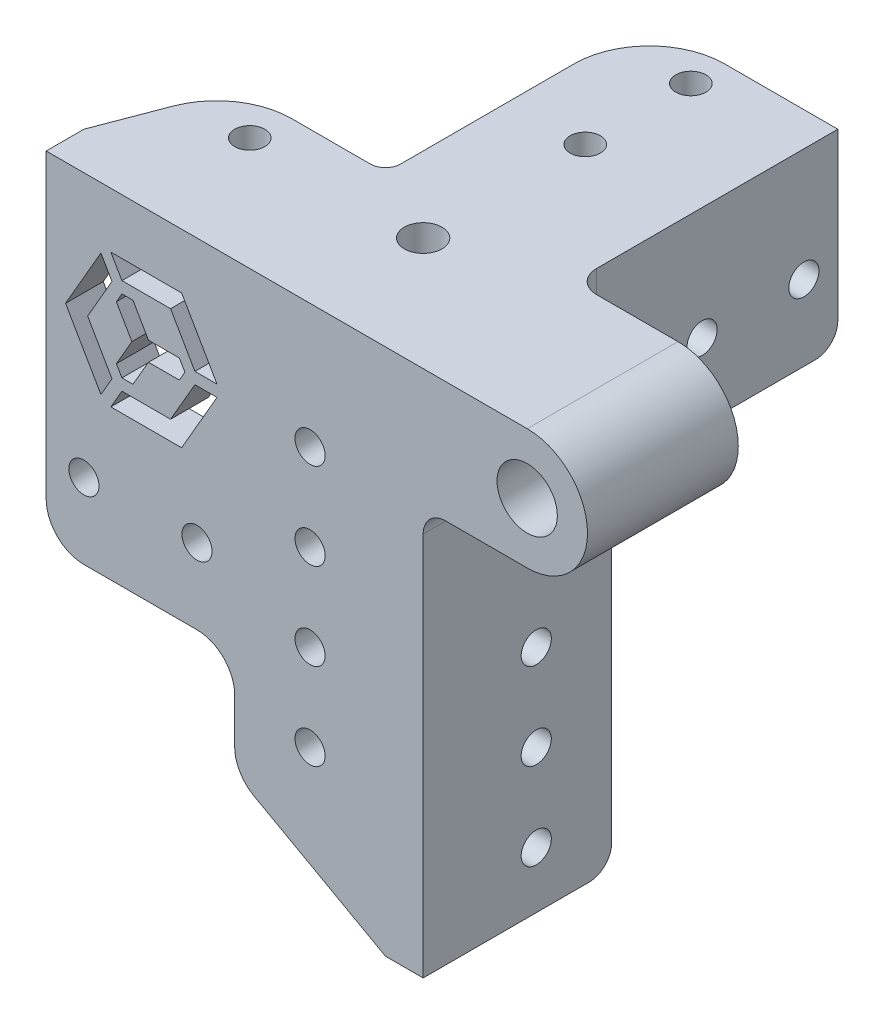
SolidWorks part; units mm, degrees
ref_plane "Front Plane" through (0, 0, 0) normal (0, 0, 1) x (1, 0, 0)
ref_plane "Top Plane" through (0, 0, 0) normal (0, 1, 0) x (1, 0, 0)
ref_plane "Right Plane" through (0, 0, 0) normal (1, 0, 0) x (0, 0, -1)
sketch "Sketch1" plane through (0, 0, 0) normal (0, 0, 1) x (1, 0, 0)
  line L0 (0, 20) -> (-25, 20)
  line L1 (0, 0) -> (-25, 0)
  line L2 (0, 0) -> (0, -20)
  line L3 (0, -20) -> (-25, -20)
  line L4 (-25, 0) -> (-25, -20)
  line L5 (0, 20) -> (20, 20)
  line L6 (0, 20) -> (0, -33.8889)
  line L8 (20, 20) -> (20, -45)
  line L9 (-25, 20) -> (-25, 0)
  line L11 (20, 20) -> (25, 20)
  line L12 (25, 20) -> (25, -45)
  line L13 (25, -45) -> (20, -45)
  line L14 (38.8, 25) -> (25, 25)
  line L15 (-25, 20) -> (25, 20)
  line L16 (-25, 20) -> (-25, 25)
  line L17 (-25, 25) -> (25, 25)
  line L18 (25, 20) -> (25, 25)
  line L19 (38.8, 9) -> (25, 9)
  line L20 (-25, -20) -> (20, -45)
  circle A0 centre (38.8, 17) radius 4
  circle A1 centre (38.8, 17) radius 8
  dimension "D10" = 8
  dimension "D11" = 4
  dimension "D1" = 20
  dimension "D2" = 20
  dimension "D3" = 20
  dimension "D4" = 25
  dimension "D5" = 65
  dimension "D6" = 5
  dimension "D7" = 5
  dimension "D8" = 18.8
  dimension "D9" = 17
extrude "Boss-Extrude2" add sketch "Sketch1" along normal blind 5
sketch "Sketch3" plane through (25, 0, 0) normal (1, 0, 0) x (0, 0, -1)
  line L0 (-5, 25) -> (0, 25) construction
  line L1 (0, -45) -> (20, -45)
  line L2 (0, -45) -> (0, 25)
  line L3 (0, 25) -> (20, 25)
  line L4 (20, -45) -> (20, 25)
  line L5 (50, 0) -> (20, -45)
  line L6 (20, 20) -> (50, 20)
  line L7 (20, 20) -> (20, 0)
  line L8 (20, 0) -> (50, 0)
  line L9 (50, 20) -> (50, 0)
  line L10 (50, 20) -> (20, 20)
  line L11 (50, 20) -> (50, 25)
  line L12 (50, 25) -> (20, 25)
  line L13 (20, 20) -> (20, 25)
  line M11 (0, -45) -> (0, 9)
  dimension "D1" = 20
  dimension "D2" = 5
  dimension "D3" = 20
  dimension "D4" = 30
extrude "Boss-Extrude3" add sketch "Sketch3" against normal blind 5 contours L8 L4 L5 | L9 L6 L4 L8 | L1 L4 L3 L2 M11 | L11 L12 L4 L6
sketch "Sketch4" plane through (0, 25, 0) normal (0, 1, 0) x (1, 0, 0)
  line L0 (20, 50) -> (25, 50) construction
  line L1 (20, 0) -> (-6, 0)
  line L2 (20, 0) -> (20, 50)
  line L3 (20, 50) -> (-6, 50)
  line L4 (-6, 0) -> (-6, 50)
  line L6 (-6, 50) -> (-25, 0)
  line M8 (20, 50) -> (20, 0)
  line M9 (20, 0) -> (-25, 0)
  dimension "D1" = 26
extrude "Boss-Extrude4" add sketch "Sketch4" against normal blind 5 contours L4 L3 M9 M8 | L4 L6 M9
sketch "Sketch5" plane through (0, 0, 0) normal (0, 0, -1) x (-1, 0, 0)
  line L3 (-38.8, 9) -> (-25, 9)
  line L4 (-25, 9) -> (-25, 25)
  line L5 (-25, 25) -> (-38.8, 25)
  line L6 (-38.8, 9) -> (-25, 9)
  line L7 (-25, 9) -> (-25, 25)
  line L8 (-25, 25) -> (-38.8, 25)
  circle A0 centre (-38.8, 17) radius 4 construction
  arc A1 (-38.8, 25) -> (-38.8, 9) centre (-38.8, 17) ccw
  arc A2 (-38.8, 25) -> (-38.8, 9) centre (-38.8, 17) ccw
  circle A3 centre (-38.8, 17) radius 4
  dimension "D1" = 0
extrude "Boss-Extrude5" add sketch "Sketch5" along normal blind 15
sketch "Sketch6" plane through (0, 25, 0) normal (0, 1, 0) x (1, 0, 0)
  line L0 (0, 0) -> (20, 20) construction
  line L1 (0, 0) -> (20, 0) construction
  line L2 (0, 0) -> (0, 20) construction
  line L3 (0, 20) -> (20, 20) construction
  line L4 (20, 0) -> (20, 20) construction
  line L5 (10, 20) -> (10, 50) construction
  line L6 (-6, 50) -> (25, 50) construction
  line L7 (0, 10) -> (-21.2, 10) construction
  line L8 (-6, 50) -> (-25, 0) construction
  circle A0 centre (10, 10) radius 2.5
  circle A1 centre (10, 45.5) radius 2
  circle A2 centre (10, 31.5) radius 2
  circle A3 centre (-13, 10) radius 2
  dimension "D3" = 5
  dimension "D4" = 4.5
  dimension "D5" = 18.5
  dimension "D6" = 4
  dimension "D7" = 4
  dimension "D8" = 23
  dimension "D9" = 4
  dimension "D1" = 20
  dimension "D2" = 20
extrude "Cut-Extrude1" cut sketch "Sketch6" against normal through all both and the other way through all
sketch "Sketch7" plane through (25, 0, 0) normal (1, 0, 0) x (0, 0, -1)
  line L0 (10, -45) -> (10, 9) construction
  line L2 (-5, 9) -> (15, 9) construction
  line L3 (-5, 9) -> (-5, -45) construction
  line L4 (50, 10) -> (15, 10) construction
  line L5 (50, 25) -> (50, 0) construction
  line L6 (15, 9) -> (15, 25) construction
  line L7 (15, 25) -> (50, 25) construction
  line L8 (-5, -45) -> (20, -45) construction
  circle A0 centre (10, -37.5) radius 2
  circle A1 centre (10, -26) radius 2
  circle A2 centre (10, -14.5) radius 2
  circle A3 centre (10, -3) radius 2
  circle A4 centre (45.5, 10) radius 2
  circle A5 centre (32, 10) radius 2
  dimension "D1" = 4
  dimension "D2" = 7.5
  dimension "D3" = 11.5
  dimension "D4" = 11.5
  dimension "D5" = 11.5
  dimension "D8" = 4.5
  dimension "D9" = 13.5
  dimension "D6" = 15
  dimension "D7" = 15
extrude "Cut-Extrude2" cut sketch "Sketch7" against normal blind 15
sketch "Sketch9" plane through (0, 0, 5) normal (0, 0, 1) x (1, 0, 0)
  line L0 (10, 25) -> (10, -39.4444) construction
  line L1 (38.8, 25) -> (-25, 25) construction
  line L2 (-25, -20) -> (20, -45) construction
  line L3 (25, 9) -> (25, -45) construction
  line L4 (25, -45) -> (20, -45) construction
  line L5 (-25, -10) -> (25, -10) construction
  line L6 (-25, -20) -> (-25, 25) construction
  circle A0 centre (10, -26) radius 2
  circle A1 centre (10, -14.5) radius 2
  circle A2 centre (10, -3) radius 2
  circle A3 centre (10, 8.5) radius 2
  circle A4 centre (-20, -10) radius 2
  circle A5 centre (-5, -10) radius 2
  dimension "D2" = 4
  dimension "D3" = 19
  dimension "D4" = 11.5
  dimension "D5" = 11.5
  dimension "D6" = 11.5
  dimension "D8" = 4
  dimension "D9" = 5
  dimension "D10" = 20
  dimension "D11" = 4
  dimension "D1" = 15
  dimension "D7" = 10
extrude "Cut-Extrude3" cut sketch "Sketch9" against normal through all
fillet "Fillet1" radius 3 2 edges at (25, 9, -5) (25, 17, -15)
ref_plane "Plane1" through (-25, 0, 0) normal (-1, 0, 0) x (0, 0, 1)
sketch "Sketch10" plane through (0, 25, 0) normal (0, 1, 0) x (1, 0, 0)
  line L0 (0, 50) -> (0, 15)
  line L1 (-6, 50) -> (25, 50) construction
  line L2 (0, 15) -> (-19.3, 15)
  line L3 (-6, 50) -> (-25, 0) construction
  line L6 (25, 18) -> (25, 50) construction
  line L8 (28, 15) -> (38.8, 15) construction
  line L9 (0, 50) -> (-6, 50)
  line L10 (-6, 50) -> (-19.3, 15)
  dimension "D1" = 25
extrude "Cut-Extrude4" cut sketch "Sketch10" against normal blind 10
fillet "Fillet2" radius 10 2 edges at (-19.3, 22.5, -15) (0, 22.5, -50)
fillet "Fillet3" radius 2 1 edges at (0, 22.5, -15)
sketch "Sketch12" plane through (20, 0, 0) normal (-1, 0, 0) x (0, 0, 1)
  line L0 (-50, 0) -> (-20, 0)
  line L1 (-20, 0) -> (-20, -45)
  line L2 (0, -45) -> (-20, -45) construction
  line L3 (-50, 0) -> (-20, -45) construction
extrude "Cut-Extrude6" cut sketch "Sketch12" against normal blind 10 and the other way through all flip side to cut
fillet "Fillet4" radius 3 3 edges at (22.5, -45, -20) (22.5, 0, -50) (22.5, 0, -20)
sketch "Sketch13" plane through (0, 0, 0) normal (0, 0, -1) x (-1, 0, 0)
  line L0 (0, -33.8889) -> (0, -20)
  line L1 (25, -20) -> (-20, -45) construction
  line L2 (0, -20) -> (25, -20)
extrude "Cut-Extrude8" cut sketch "Sketch13" against normal through all flip side to cut
fillet "Fillet5" radius 5 3 edges at (0, -33.8889, 2.5) (-25, -20, 2.5) (0, -20, 2.5)
sketch "Sketch11" plane through (0, 0, 0) normal (0, 0, -1) x (-1, 0, 0)
  line L0 (22.4344, 8.7823) -> (17.3018, 17.6723)
  line L1 (17.3018, 17.6723) -> (7.0365, 17.6723)
  line L2 (7.0365, 17.6723) -> (1.9038, 8.7823)
  line L3 (1.9038, 8.7823) -> (7.0365, -0.1077)
  line L4 (7.0365, -0.1077) -> (17.3018, -0.1077)
  line L5 (17.3018, -0.1077) -> (22.4344, 8.7823)
  line L6 (8.5029, 15.1323) -> (4.8368, 8.7823)
  line L7 (4.8368, 8.7823) -> (8.5029, 2.4323)
  line L8 (8.5029, 2.4323) -> (15.8353, 2.4323)
  line L9 (15.8353, 2.4323) -> (19.5015, 8.7823)
  line L10 (19.5015, 8.7823) -> (15.8353, 15.1323)
  line L11 (15.8353, 15.1323) -> (8.5029, 15.1323)
  line L12 (13.4889, 13.6083) -> (11.4359, 10.0523)
  line L13 (11.4359, 10.0523) -> (7.3298, 10.0523)
  line L14 (7.3298, 10.0523) -> (6.5965, 8.7823)
  line L15 (6.5965, 8.7823) -> (7.3298, 7.5123)
  line L16 (7.3298, 7.5123) -> (11.4359, 7.5123)
  line L17 (11.4359, 7.5123) -> (13.4889, 3.9563)
  line L18 (13.4889, 3.9563) -> (14.9554, 3.9563)
  line L19 (14.9554, 13.6083) -> (13.4889, 13.6083)
  line L20 (14.9554, 13.6083) -> (15.6886, 12.3383)
  line L21 (15.6886, 12.3383) -> (13.6356, 8.7823)
  line L22 (13.6356, 8.7823) -> (15.6886, 5.2263)
  line L23 (15.6886, 5.2263) -> (14.9554, 3.9563)
  line L24 (14.9554, 15.1323) -> (16.4219, 17.6723)
  line L25 (17.7417, 16.9103) -> (16.4219, 17.6723) construction
  line L26 (17.7417, 16.9103) -> (16.2752, 14.3703)
  line L27 (16.4219, 17.6723) -> (17.3018, 17.6723) construction
  line L28 (15.8353, 15.1323) -> (17.3018, 17.6723) construction
  line L29 (30.4571, 8.7823) -> (22.4344, 8.7823) construction
  line L30 (14.9554, 2.4323) -> (16.4219, -0.1077)
  line L31 (17.7417, 0.6543) -> (16.2752, 3.1943)
  line L32 (7.0365, 17.6723) -> (8.5029, 15.1323) construction
  line L33 (2.3438, 8.0203) -> (5.2767, 8.0203)
  line L34 (5.2767, 9.5443) -> (2.3438, 9.5443)
  circle A0 centre (12.1691, 8.7823) radius 8.89 construction
  dimension "D1" = 17.78
  dimension "D2" = 1.524
  dimension "D3" = 1.524
  dimension "D4" = 1.524
  dimension "D5" = 1.524
  dimension "D6" = 1.524
  dimension "D7" = 2.54
  dimension "D8" = 1.524
extrude "Cut-Extrude5" cut sketch "Sketch11" against normal blind 10 contours L33 L3 L4 L30 L8 L7 | L34 L6 L11 L24 L1 L2 | L31 L5 L0 L26 L10 L9 | L23 L22 L21 L20 L19 L12 L13 L14 L15 L16 L17 L18
sketch "Sketch14" plane through (0, 0, 5) normal (0, 0, 1) x (1, 0, 0)
  line L0 (-26.1352, -8.754) -> (12.4969, 9.5704) construction
  text T0 "691" font "Stencil" height in points 45
  point P2 (-27.0702, 6.5416)
  point P3 (-26.4006, -6.4646)
  point P5 (-25, 11.5518)
  point P6 (0, 0)
  point P7 (0.461, -5.8872)
  point P8 (-25, 9.7)
  point P9 (-25, 9.4037)
  point P10 (7.1303, 15.6065)
  point P11 (-25, -4.6327)
  point P12 (14.6623, 15.2942)
  point P13 (15.1196, 13.9303)
  point P14 (-25, -9.2738)
  point P15 (7.2876, 12.1867)
  point P16 (-25, -9.6923)
  point P17 (12, 10.5)
  point P18 (13.4857, 10.2587)
  point P19 (-25, 10.2587)
  point P20 (1.7591, -10.9186)
  point P21 (1.1683, -7.9534)
  point P22 (-25, 5.9798)
  point P23 (2.9511, -8.9009)
  point P24 (3.1862, -7.7259)
  point P25 (0, 0)
  point P26 (0, 0)
  point P27 (7.9254, 7.2748)
  point P28 (-16.5871, -8.7654)
  point P29 (-21.181, -8.3859)
  point P30 (-23.2088, -8.4299)
  point P31 (-23.9304, -8.09)
  point P32 (-21.486, -8.6614)
  point P33 (8, 7.1629)
  point P34 (9.782, 8.3573)
  point P35 (12.4969, 9.5704)
  point P36 (-27.0993, -9.3484)
  point P37 (-26.1352, -8.754)
extrude "Cut-Extrude9" [suppressed] cut sketch "Sketch14" against normal blind 10
